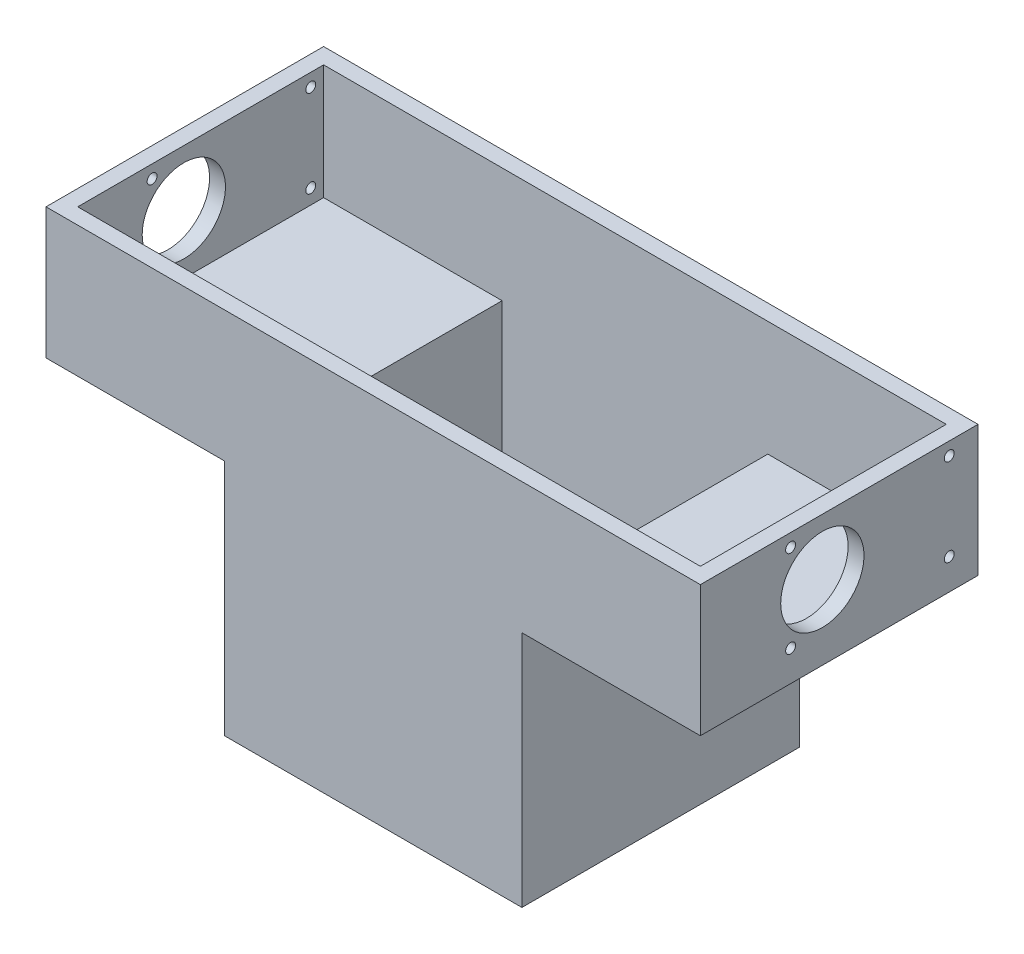
SolidWorks part; units mm, degrees
ref_plane "Front Plane" through (0, 0, 0) normal (0, 0, 1) x (1, 0, 0)
ref_plane "Top Plane" through (0, 0, 0) normal (0, 1, 0) x (1, 0, 0)
ref_plane "Right Plane" through (0, 0, 0) normal (1, 0, 0) x (0, 0, -1)
sketch "Sketch1" plane through (0, 0, 0) normal (0, 1, 0) x (1, 0, 0)
  line L0 (0, 0) -> (0, -14.43) construction
  line L1 (-37.5, 20) -> (37.5, 20)
  line L2 (-37.5, 20) -> (-37.5, -20)
  line L3 (-37.5, -20) -> (37.5, -20)
  line L4 (37.5, 20) -> (37.5, -20)
  line L5 (-37.5, 20) -> (37.5, -20) construction
  line L6 (-37.5, -20) -> (37.5, 20) construction
  line L7 (0, 0) -> (6.508, 0) construction
  line L8 (-2.5, 10) -> (2.5, 10)
  line L9 (-2.5, 10) -> (-2.5, -10)
  line L10 (-2.5, -10) -> (2.5, -10)
  line L11 (2.5, 10) -> (2.5, -10)
  line L12 (-2.5, 10) -> (2.5, -10) construction
  line L13 (-2.5, -10) -> (2.5, 10) construction
  circle A0 centre (-21, 0) radius 5
  circle A1 centre (-30, 8.25) radius 1.7
  circle A2 centre (-12, 8.25) radius 1.7
  circle A3 centre (-12, -8.25) radius 1.7
  circle A4 centre (-30, -8.25) radius 1.7
  circle A5 centre (12, 8.25) radius 1.7
  circle A6 centre (12, -8.25) radius 1.7
  circle A7 centre (21, 0) radius 5
  circle A8 centre (30, -8.25) radius 1.7
  circle A9 centre (30, 8.25) radius 1.7
  circle A10 centre (-30, -17.5) radius 1.1976
  circle A11 centre (-12, -17.5) radius 1.1976
  circle A12 centre (12, -17.5) radius 1.1976
  circle A13 centre (30, -17.5) radius 1.1976
  circle A14 centre (30, 17.5) radius 1.1976
  circle A15 centre (12, 17.5) radius 1.1976
  circle A16 centre (-12, 17.5) radius 1.1976
  circle A17 centre (-30, 17.5) radius 1.1976
  point P0 (0, 0)
  dimension "D3" = 10
  dimension "D4" = 21
  dimension "D5" = 8.25
  dimension "D6" = 9
  dimension "D9" = 5
  dimension "D11" = 20
  dimension "D12" = 7.5
  dimension "D13" = 25.5
  dimension "D14" = 7.5
  dimension "D15" = 2.5
  dimension "D1" = 75
  dimension "D2" = 40
  dimension "D10" = 20
  dimension "D7" = 2
  dimension "D8" = 2
  dimension "D16" = 2
extrude "Boss-Extrude1" add sketch "Sketch1" along normal blind 3
sketch "Sketch2" plane through (0, 3, 0) normal (0, 1, 0) x (1, 0, 0)
  line L0 (-37.5, 20) -> (-37.5, -20) construction
  line L1 (-33.5, 14) -> (33.5, 14)
  line L2 (-33.5, 14) -> (-33.5, -14)
  line L3 (-33.5, -14) -> (33.5, -14)
  line L4 (33.5, 14) -> (33.5, -14)
  line L5 (37.5, -20) -> (37.5, 20) construction
  line L6 (37.5, 20) -> (-37.5, 20) construction
  line L7 (-37.5, -20) -> (37.5, -20) construction
  dimension "D1" = 4
  dimension "D2" = 4
  dimension "D3" = 6
  dimension "D4" = 6
extrude "Cut-Extrude1" cut sketch "Sketch2" against normal through all both and the other way through all
sketch "Sketch3" plane through (0, 3, 0) normal (0, 1, 0) x (1, 0, 0)
  line L1 (37.5, 20) -> (-37.5, 20)
  line L2 (37.5, 20) -> (37.5, 35)
  line L3 (37.5, 35) -> (-37.5, 35)
  line L4 (-37.5, 20) -> (-37.5, 35)
  line L5 (-37.5, -20) -> (37.5, -20)
  line L6 (-37.5, -20) -> (-37.5, -35)
  line L7 (-37.5, -35) -> (37.5, -35)
  line L8 (37.5, -20) -> (37.5, -35)
  line L10 (-37.5, 20) -> (-33.5, 20)
  line L11 (-37.5, 20) -> (-37.5, -20)
  line L12 (-37.5, -20) -> (-33.5, -20)
  line L13 (-33.5, 20) -> (-33.5, -20)
  line L14 (37.5, 20) -> (33.5, 20)
  line L15 (37.5, 20) -> (37.5, -20)
  line L16 (37.5, -20) -> (33.5, -20)
  line L17 (33.5, 20) -> (33.5, -20)
  line M3 (-33.5, -14) -> (-33.5, 14)
  line M5 (33.5, 14) -> (33.5, -14)
  line M11 (37.5, -20) -> (37.5, 20)
  line M12 (37.5, 20) -> (-37.5, 20)
  line M13 (-37.5, 20) -> (-37.5, -20)
  line M14 (-37.5, -20) -> (37.5, -20)
  dimension "D1" = 15
  dimension "D2" = 15
extrude "Boss-Extrude3" add sketch "Sketch3" along normal blind 90 and the other way blind 3 contours L8 L5 L6 L7 M14 | L4 L1 L2 L3 M12 | L17 M12 M5 M14 M11 | L13 L1 M13 M14 M3
sketch "Sketch6" plane through (0, 3, 0) normal (0, 1, 0) x (1, 0, 0)
  line L0 (-37.5, -35) -> (37.5, -35) construction
  line L1 (-33.5, -20) -> (33.5, -20)
  line L2 (-33.5, -20) -> (-33.5, -31)
  line L3 (-33.5, -31) -> (33.5, -31)
  line L4 (33.5, -20) -> (33.5, -31)
  line L5 (33.5, 20) -> (-33.5, 20)
  line L6 (33.5, 20) -> (33.5, 31)
  line L7 (33.5, 31) -> (-33.5, 31)
  line L8 (-33.5, 20) -> (-33.5, 31)
  line L9 (37.5, 35) -> (-37.5, 35) construction
  dimension "D1" = 4
  dimension "D2" = 4
extrude "Cut-Extrude4" cut sketch "Sketch6" along normal through all
sketch "Sketch7" plane through (-37.5, 0, 0) normal (-1, 0, 0) x (0, 0, 1)
  line L0 (35, 0) -> (35, 93) construction
  line L1 (-35, 93) -> (35, 93)
  line L2 (-35, 93) -> (-35, 56)
  line L3 (-35, 56) -> (35, 56)
  line L4 (35, 93) -> (35, 56)
  dimension "D1" = 37
extrude "Boss-Extrude4" add sketch "Sketch7" along normal blind 45
ref_plane "Plane1" through (0, 0, 0) normal (1, 0, 0) x (0, 0, -1)
mirror "Mirror2" about plane through (0, 0, 0) normal (1, 0, 0) of "Boss-Extrude4"
sketch "Sketch8" plane through (0, 93, 0) normal (0, 1, 0) x (1, 0, 0)
  line L0 (-82.5, -35) -> (-82.5, 35) construction
  line L1 (-33.5, 31) -> (-78.5, 31)
  line L2 (-33.5, 31) -> (-33.5, -31)
  line L3 (-33.5, -31) -> (-78.5, -31)
  line L4 (-78.5, 31) -> (-78.5, -31)
  line L5 (33.5, -31) -> (78.5, -31)
  line L6 (33.5, -31) -> (33.5, 31)
  line L7 (33.5, 31) -> (78.5, 31)
  line L8 (78.5, -31) -> (78.5, 31)
  line L9 (82.5, -35) -> (82.5, 35) construction
  dimension "D1" = 4
  dimension "D2" = 4
extrude "Cut-Extrude6" cut sketch "Sketch8" against normal blind 29
sketch "Sketch9" plane through (-82.5, 0, 0) normal (-1, 0, 0) x (0, 0, 1)
  line L0 (35, 93) -> (-35, 93) construction
  line L2 (15.5, 64.5) -> (-31, 64.5)
  line L3 (15.5, 64.5) -> (15.5, 93)
  line L4 (15.5, 93) -> (-31, 93)
  line L5 (-31, 64.5) -> (-31, 93)
  line L6 (-31, 64) -> (-31, 93) construction
  circle A0 centre (4.25, 78.75) radius 10.5
  circle A1 centre (12.25, 89.75) radius 1.25
  circle A2 centre (-27.75, 89.75) radius 1.25
  circle A3 centre (-27.75, 67.75) radius 1.25
  circle A4 centre (12.25, 67.75) radius 1.25
  point P16 (0, 0)
  dimension "D1" = 14.25
  dimension "D2" = 21
  dimension "D3" = 2.5
  dimension "D4" = 3.25
  dimension "D5" = 8
  dimension "D11" = 3.25
  dimension "D8" = 28.5
  dimension "D9" = 46.5
  dimension "D10" = 0
  dimension "D6" = 2
  dimension "D7" = 2
extrude "Cut-Extrude8" cut sketch "Sketch9" against normal through all contours A2 | A3 | A0 | A4 | A1
sketch "Sketch11" plane through (0, 0, 35) normal (0, 0, 1) x (1, 0, 0)
  line L0 (82.5, 56) -> (82.5, 93) construction
  line L1 (-82.5, 56) -> (-37.5, 56)
  line L2 (-82.5, 56) -> (-82.5, 60)
  line L3 (-82.5, 60) -> (-37.5, 60)
  line L4 (-37.5, 56) -> (-37.5, 60)
  line L5 (37.5, 56) -> (82.5, 56)
  line L6 (37.5, 56) -> (37.5, 60)
  line L7 (37.5, 60) -> (82.5, 60)
  line L8 (82.5, 56) -> (82.5, 60)
  line L11 (-78.5, 64) -> (-33.5, 64) construction
  line L12 (33.5, 64) -> (78.5, 64) construction
  dimension "D1" = 4
  dimension "D2" = 4
extrude "Cut-Extrude9" cut sketch "Sketch11" against normal through all
